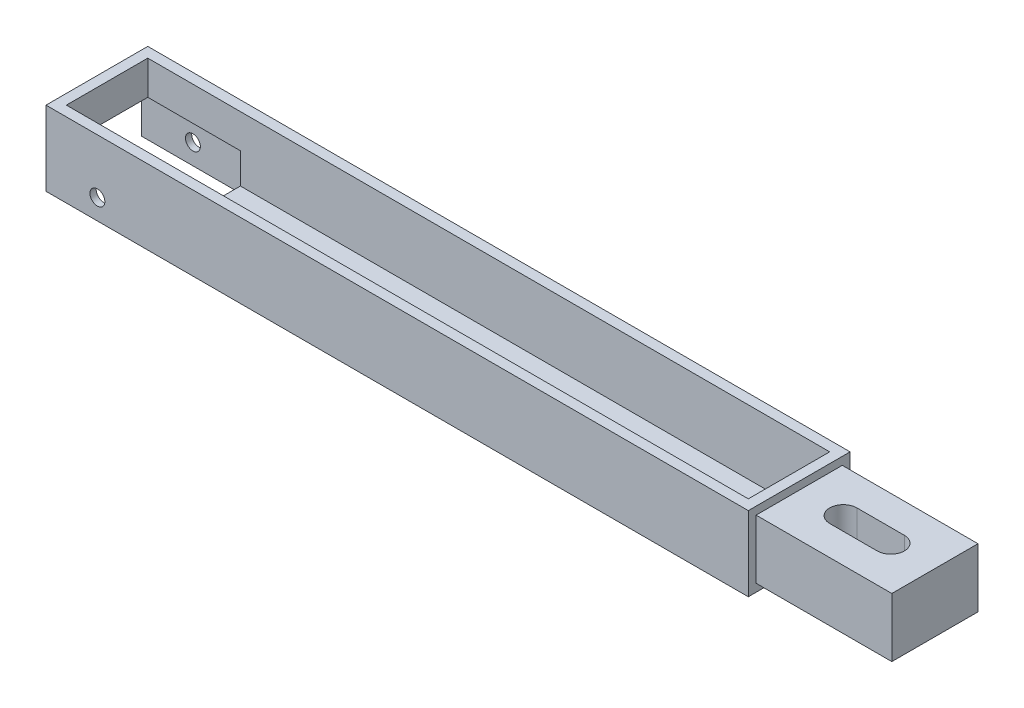
SolidWorks part; units mm, degrees
ref_plane "Front Plane" through (0, 0, 0) normal (0, 0, 1) x (1, 0, 0)
ref_plane "Top Plane" through (0, 0, 0) normal (0, 1, 0) x (1, 0, 0)
ref_plane "Right Plane" through (0, 0, 0) normal (1, 0, 0) x (0, 0, -1)
sketch "Sketch1" plane through (0, 0, 0) normal (0, 1, 0) x (1, 0, 0)
  line L1 (-103.5, -15) -> (103.5, -15)
  line L2 (-103.5, -15) -> (-103.5, 15)
  line L3 (-103.5, 15) -> (103.5, 15)
  line L4 (103.5, -15) -> (103.5, 15)
  line L5 (-103.5, -15) -> (103.5, 15) construction
  line L6 (-103.5, 15) -> (103.5, -15) construction
  point P0 (0, 0)
  dimension "D1" = 207
  dimension "D2" = 30
extrude "Boss-Extrude1" add sketch "Sketch1" along normal blind 22
shell "Shell1" thickness 3
sketch "Sketch2" plane through (0, 0, 0) normal (0, -1, 0) x (-1, 0, 0)
  line L0 (103.5, -15) -> (-103.5, -15) construction
  line L1 (-103.5, 5) -> (103.5, 5)
  line L2 (-103.5, 5) -> (-103.5, -5)
  line L3 (-103.5, -5) -> (103.5, -5)
  line L4 (103.5, 5) -> (103.5, -5)
  line L5 (-103.5, 5) -> (103.5, -5) construction
  line L6 (-103.5, -5) -> (103.5, 5) construction
  line L7 (103.5, 15) -> (103.5, -15) construction
  line L8 (-103.5, -15) -> (-103.5, 15) construction
  point P0 (0, 0)
  dimension "D1" = 10
  dimension "D2" = 15
  dimension "D3" = 0
  dimension "D4" = 0
extrude "Cut-Extrude1" cut sketch "Sketch2" against normal blind 3
sketch "Sketch3" plane through (0, 0, 0) normal (0, -1, 0) x (-1, 0, 0)
  line L0 (103.5, -5) -> (103.5, -15) construction
  line L1 (73.2, 13.15) -> (103.5, 13.15)
  line L2 (73.2, 13.15) -> (73.2, -13.15)
  line L3 (73.2, -13.15) -> (103.5, -13.15)
  line L4 (103.5, 13.15) -> (103.5, -13.15)
  line L5 (73.2, 13.15) -> (103.5, -13.15) construction
  line L6 (73.2, -13.15) -> (103.5, 13.15) construction
  line L7 (-103.5, 15) -> (103.5, 15) construction
  point P0 (88.35, 0)
  point P7 (0, 0)
  dimension "D1" = 30.3
  dimension "D2" = 26.3
  dimension "D3" = 15.15
  dimension "D4" = 15
extrude "Cut-Extrude2" cut sketch "Sketch3" against normal blind 12
sketch "Sketch4" plane through (0, 0, 15) normal (0, 0, 1) x (1, 0, 0)
  line L0 (-103.5, 22) -> (-103.5, 0) construction
  line L1 (-103.5, 0) -> (103.5, 0) construction
  circle A0 centre (-88.35, 6) radius 2.2
  dimension "D1" = 4.4
  dimension "D2" = 15.15
  dimension "D3" = 6
extrude "Cut-Extrude3" cut sketch "Sketch4" against normal through all
sketch "Sketch5" plane through (103.5, 0, 0) normal (1, 0, 0) x (0, 0, -1)
  line L0 (0, 22) -> (0, 0) construction
  line L1 (-15, 22) -> (15, 22) construction
  line L2 (12.7, 19.7) -> (-12.7, 19.7)
  line L3 (12.7, 19.7) -> (12.7, 2.3)
  line L4 (12.7, 2.3) -> (-12.7, 2.3)
  line L5 (-12.7, 19.7) -> (-12.7, 2.3)
  line L6 (12.7, 19.7) -> (-12.7, 2.3) construction
  line L7 (12.7, 2.3) -> (-12.7, 19.7) construction
  line L8 (-15, 11) -> (15, 11) construction
  line L9 (-15, 22) -> (-15, 0) construction
  line L10 (15, 22) -> (15, 0) construction
  point P1 (0, 11)
  point P16 (0, 11)
  dimension "D1" = 25.4
  dimension "D2" = 17.4
extrude "Boss-Extrude2" add sketch "Sketch5" along normal blind 40
sketch "Sketch6" plane through (0, 19.7, 0) normal (0, 1, 0) x (1, 0, 0)
  line L0 (116.5, 0) -> (130.5, 0) construction
  line L1 (116.5, 4) -> (130.5, 4)
  line L2 (116.5, -4) -> (130.5, -4)
  line L3 (143.5, 12.7) -> (143.5, -12.7) construction
  arc A0 (116.5, 4) -> (116.5, -4) centre (116.5, 0) ccw
  arc A1 (130.5, -4) -> (130.5, 4) centre (130.5, 0) ccw
  point P3 (123.5, 0)
  dimension "D1" = 8
  dimension "D2" = 14
  dimension "D3" = 20
extrude "Cut-Extrude4" cut sketch "Sketch6" against normal through all
